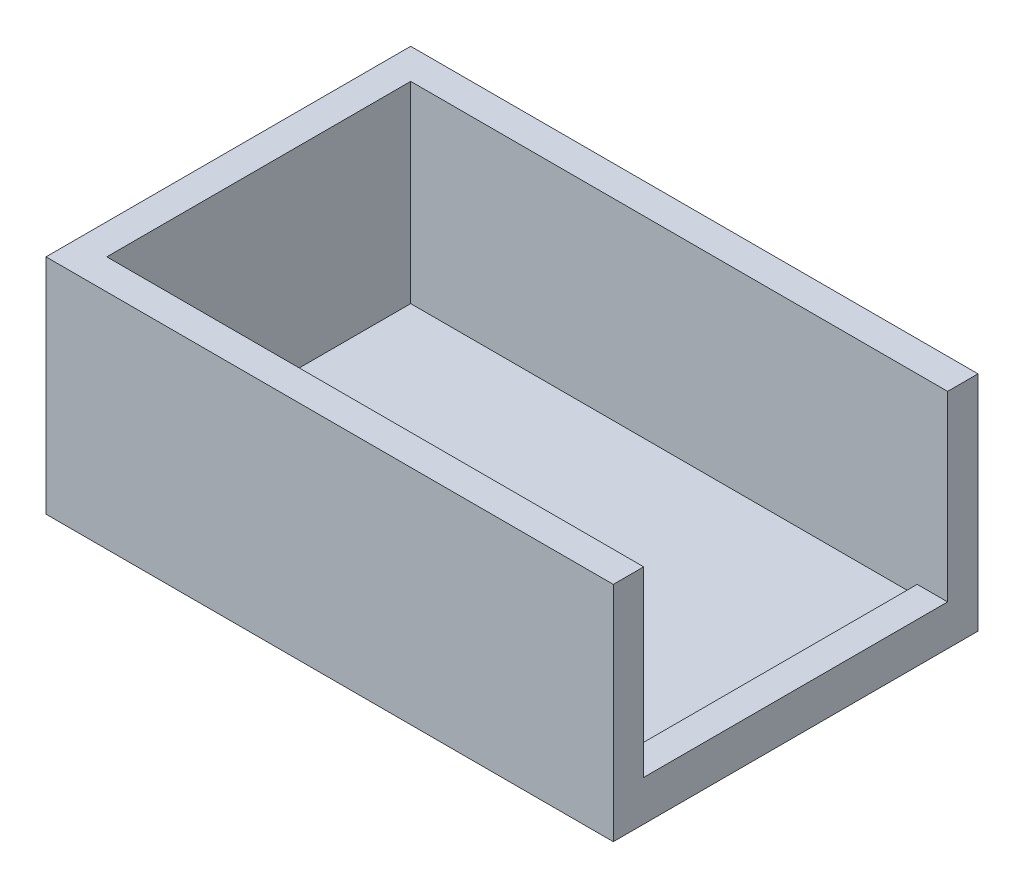
SolidWorks part; units mm, degrees
ref_plane "Front Plane" through (0, 0, 0) normal (0, 0, 1) x (1, 0, 0)
ref_plane "Top Plane" through (0, 0, 0) normal (0, 1, 0) x (1, 0, 0)
ref_plane "Right Plane" through (0, 0, 0) normal (1, 0, 0) x (0, 0, -1)
sketch "Sketch1" plane through (0, 0, 0) normal (0, 1, 0) x (1, 0, 0)
  line L1 (-28, 18) -> (28, 18)
  line L2 (-28, 18) -> (-28, -18)
  line L3 (-28, -18) -> (28, -18)
  line L4 (28, 18) -> (28, -18)
  dimension "D1" = 56
  dimension "D2" = 36
extrude "Boss-Extrude1" add sketch "Sketch1" along normal blind 22
sketch "Sketch3" plane through (0, 22, 0) normal (0, 1, 0) x (1, 0, 0)
  line L1 (-25, 15) -> (25, 15)
  line L2 (-25, 15) -> (-25, -15)
  line L3 (-25, -15) -> (25, -15)
  line L4 (25, 15) -> (25, -15)
extrude "Cut-Extrude1" cut sketch "Sketch3" against normal blind 19
sketch "Sketch4" plane through (0, 22, 0) normal (0, 1, 0) x (1, 0, 0)
  line L0 (28, -18) -> (28, 18) construction
  line L1 (25, 15) -> (28, 15)
  line L2 (25, 15) -> (25, -15)
  line L3 (25, -15) -> (28, -15)
  line L4 (28, 15) -> (28, -15)
extrude "Cut-Extrude2" cut sketch "Sketch4" against normal blind 18
